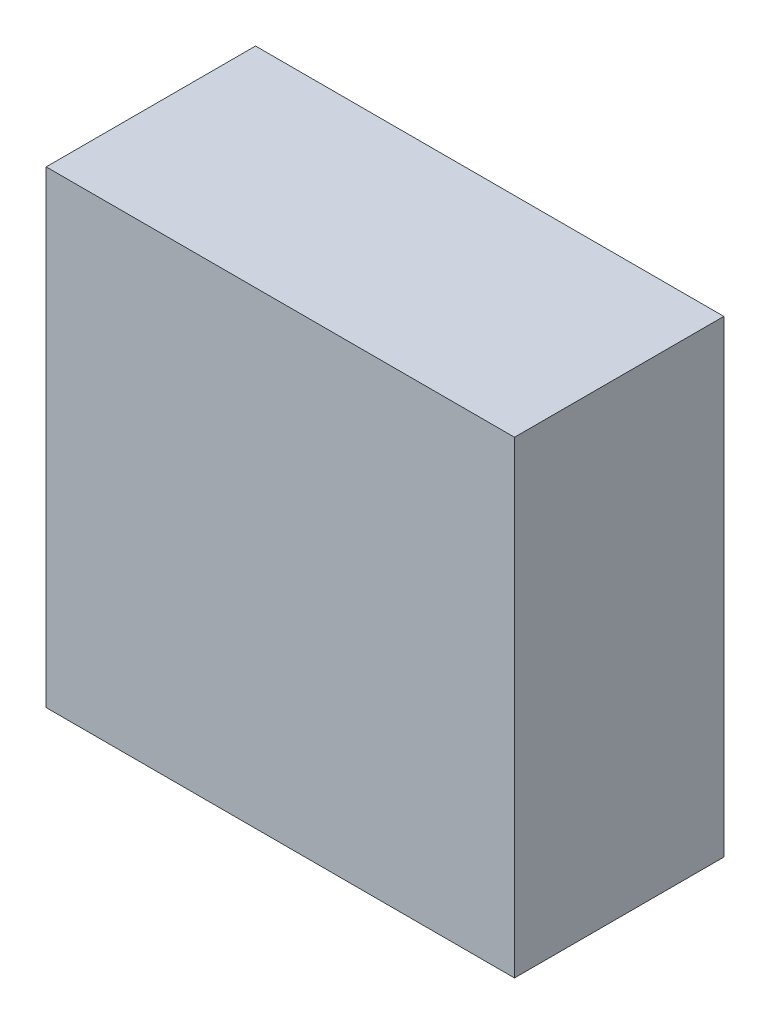
SolidWorks part; units mm, degrees
ref_plane "Plano frontal" through (0, 0, 0) normal (0, 0, 1) x (1, 0, 0)
ref_plane "Plano superior" through (0, 0, 0) normal (0, 1, 0) x (1, 0, 0)
ref_plane "Plano direito" through (0, 0, 0) normal (1, 0, 0) x (0, 0, -1)
sketch "Esboço1" plane through (0, 0, 0) normal (0, 0, 1) x (1, 0, 0)
  line L1 (11.185, -11.185) -> (-11.185, -11.185)
  line L2 (11.185, -11.185) -> (11.185, 11.185)
  line L3 (11.185, 11.185) -> (-11.185, 11.185)
  line L4 (-11.185, -11.185) -> (-11.185, 11.185)
  line L5 (11.185, -11.185) -> (-11.185, 11.185) construction
  line L6 (11.185, 11.185) -> (-11.185, -11.185) construction
  point P0 (0, 0)
  dimension "D1" = 22.37
  dimension "D2" = 22.37
extrude "Ressalto-extrusão1" add sketch "Esboço1" along normal blind 10
